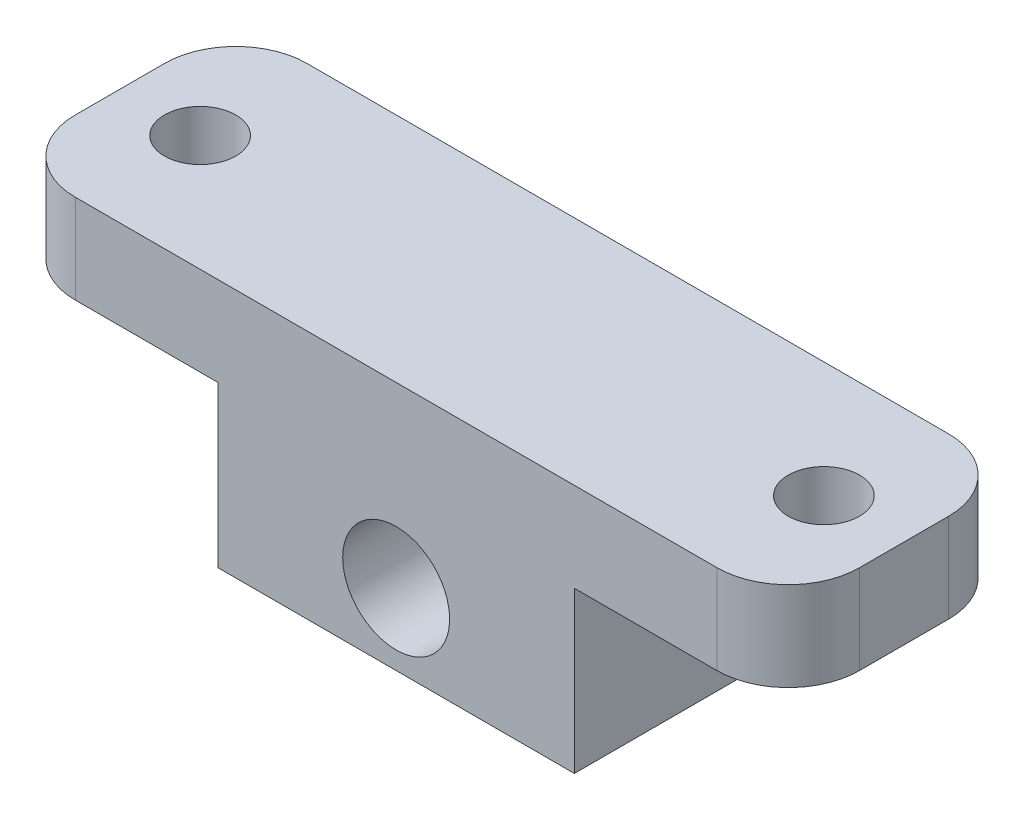
SolidWorks part; units mm, degrees
ref_plane "Front Plane" through (0, 0, 0) normal (0, 0, 1) x (1, 0, 0)
ref_plane "Top Plane" through (0, 0, 0) normal (0, 1, 0) x (1, 0, 0)
ref_plane "Right Plane" through (0, 0, 0) normal (1, 0, 0) x (0, 0, -1)
sketch "Sketch1" plane through (0, 0, 0) normal (0, 0, 1) x (1, 0, 0)
  line L0 (0, 0) -> (0, 37.7268) construction
  line L2 (-5, 16.8634) -> (5, 16.8634)
  line L3 (-5, 16.8634) -> (-5, 20.8634)
  line L4 (-5, 20.8634) -> (5, 20.8634)
  line L5 (5, 16.8634) -> (5, 20.8634)
  line L6 (-5, 16.8634) -> (5, 20.8634) construction
  line L7 (-5, 20.8634) -> (5, 16.8634) construction
  line L12 (-5, 23.8634) -> (5, 23.8634)
  line L13 (-5, 23.8634) -> (-5, 20.8634)
  line L14 (-5, 20.8634) -> (5, 20.8634)
  line L15 (5, 23.8634) -> (5, 20.8634)
  line L16 (-5, 23.8634) -> (5, 20.8634) construction
  line L17 (-5, 20.8634) -> (5, 23.8634) construction
  circle A0 centre (0, 18.8634) radius 1.5
  point P3 (0, 18.8634)
  point P8 (0, 22.3634)
  dimension "D6" = 3
  dimension "D1" = 37.7268
  dimension "D2" = 10
  dimension "D3" = 4
  dimension "D4" = 10
  dimension "D5" = 3
extrude "Boss-Extrude1" add sketch "Sketch1" along normal blind 6.5 contours L15 L12 L13 L4 | L2 L5 L4 L3
sketch "Sketch12" plane through (0, 23.8634, 0) normal (0, 1, 0) x (1, 0, 0)
  line L0 (0, -7.1805) -> (0, 0.6805) construction
  line L1 (0, -3.25) -> (6.3207, -3.25) construction
  line L2 (-5, 0) -> (5, 0) construction
  line L3 (-11, -6.5) -> (11, -6.5)
  line L4 (-11, -6.5) -> (-11, 0)
  line L5 (-11, 0) -> (11, 0)
  line L6 (11, -6.5) -> (11, 0)
  line L7 (-11, -6.5) -> (11, 0) construction
  line L8 (-11, 0) -> (11, -6.5) construction
  circle A0 centre (-8.75, -3.25) radius 1
  circle A1 centre (8.75, -3.25) radius 1
  dimension "D4" = 2
  dimension "D5" = 2.25
  dimension "D6" = 3.25
  dimension "D1" = 22
  dimension "D2" = 6.5
  dimension "D3" = 0
extrude "Boss-Extrude2" add sketch "Sketch12" against normal blind 2.5
fillet "Fillet1" radius 2 4 edges at (-11, 22.6134, 0) (-11, 22.6134, 6.5) (11, 22.6134, 6.5) (11, 22.6134, 0)
